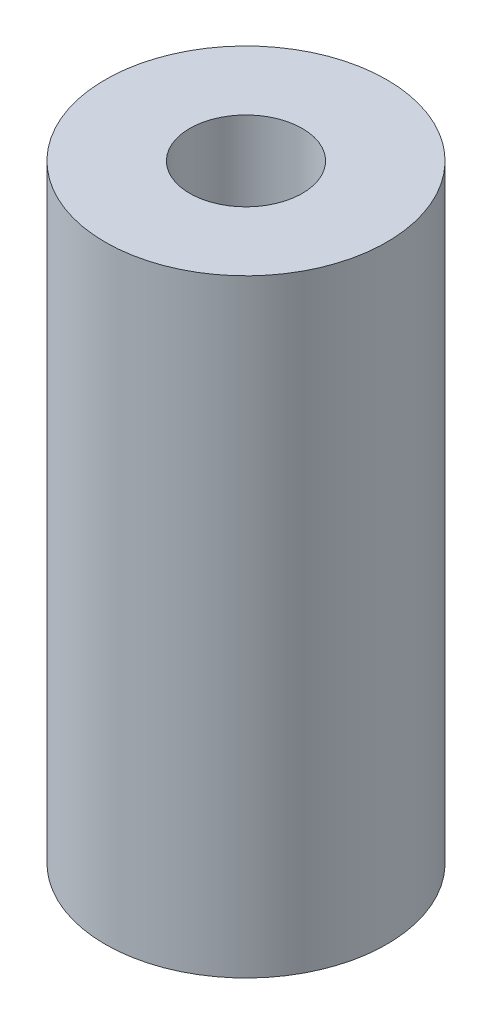
SolidWorks part; units mm, degrees
material "PLA"
ref_plane "前视基准面" through (0, 0, 0) normal (0, 0, 1) x (1, 0, 0)
ref_plane "上视基准面" through (0, 0, 0) normal (0, 1, 0) x (1, 0, 0)
ref_plane "右视基准面" through (0, 0, 0) normal (1, 0, 0) x (0, 0, -1)
sketch "草图1" plane through (0, 0, 0) normal (0, 1, 0) x (1, 0, 0)
  circle A0 centre (0, 0) radius 2.5
  circle A1 centre (0, 0) radius 1
  dimension "D1" = 2
  dimension "D2" = 5
extrude "凸台-拉伸1" add sketch "草图1" along normal blind 10.8
